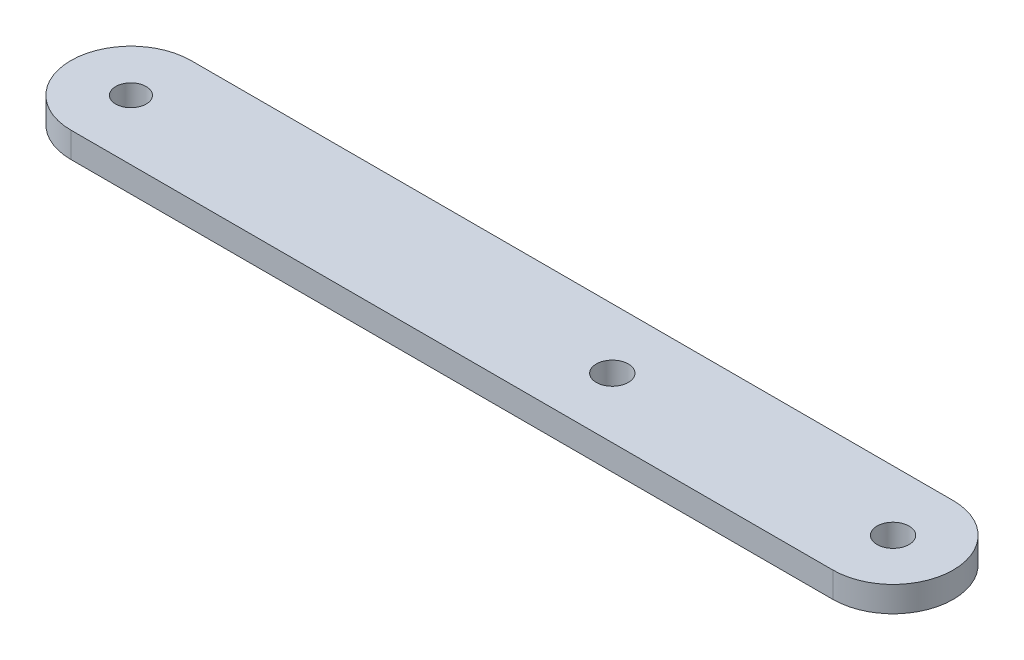
SolidWorks part; units mm, degrees
ref_plane "Front Plane" through (0, 0, 0) normal (0, 0, 1) x (1, 0, 0)
ref_plane "Top Plane" through (0, 0, 0) normal (0, 1, 0) x (1, 0, 0)
ref_plane "Right Plane" through (0, 0, 0) normal (1, 0, 0) x (0, 0, -1)
sketch "Sketch1" plane through (0, 0, 0) normal (0, 1, 0) x (1, 0, 0)
  line L7 (0, 0) -> (95, 0) construction
  line L8 (0, 7.5) -> (95, 7.5)
  line L9 (0, -7.5) -> (95, -7.5)
  circle A1 centre (0, 0) radius 1.9
  arc A2 (0, -7.5) -> (0, 7.5) centre (0, 0) ccw construction
  circle A5 centre (0, 0) radius 11.725 construction
  arc A8 (0, 7.5) -> (0, -7.5) centre (0, 0) ccw
  arc A9 (95, -7.5) -> (95, 7.5) centre (95, 0) ccw
  circle A10 centre (60, 0) radius 2
  circle A11 centre (95, 0) radius 2
  point P5 (60.0015, -0.3207)
  point P10 (95.7604, 0)
  point P11 (60, 0)
  point P17 (47.5, 0)
  dimension "D1" = 3.8
  dimension "D2" = 15
  dimension "D5" = 35
  dimension "D9" = 23.45
  dimension "D3" = 4
  dimension "D4" = 95
extrude "Boss-Extrude1" add sketch "Sketch1" along normal blind 3.175
